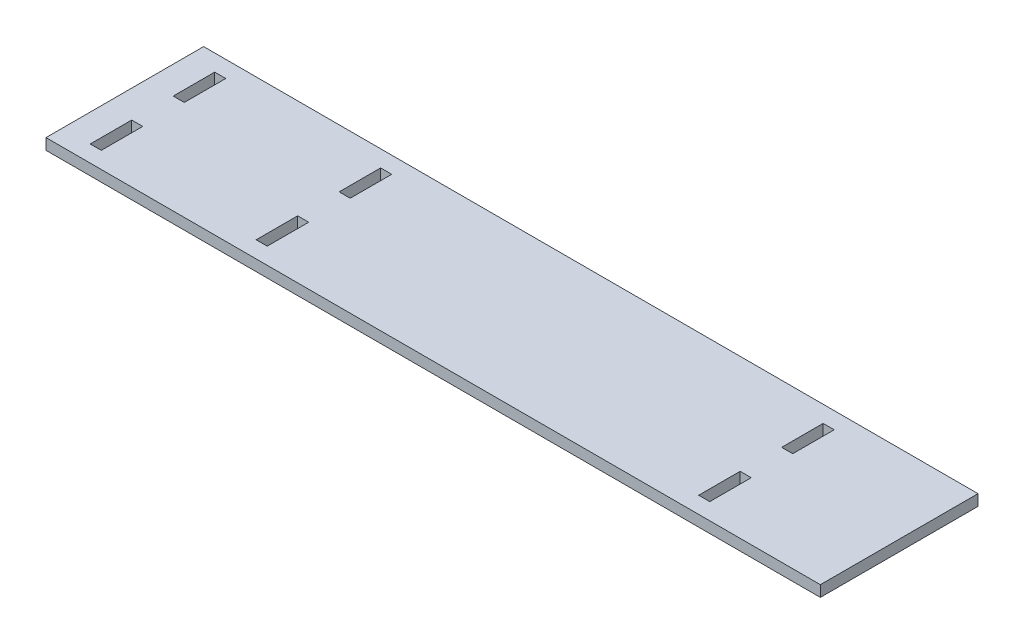
SolidWorks part; units mm, degrees
ref_plane "Front Plane" through (0, 0, 0) normal (0, 0, 1) x (1, 0, 0)
ref_plane "Top Plane" through (0, 0, 0) normal (0, 1, 0) x (1, 0, 0)
ref_plane "Right Plane" through (0, 0, 0) normal (1, 0, 0) x (0, 0, -1)
sketch "Sketch1" plane through (0, 0, 0) normal (0, 1, 0) x (1, 0, 0)
  line L1 (0, 0) -> (280, 0)
  line L2 (0, 0) -> (0, 65)
  line L3 (0, 65) -> (280, 65)
  line L4 (280, 0) -> (280, 65)
  dimension "D1" = 65
  dimension "D2" = 280
extrude "Boss-Extrude1" add sketch "Sketch1" along normal blind 4
sketch "Sketch2" plane through (0, 4, 0) normal (0, 1, 0) x (1, 0, 0)
  line L0 (0, 0) -> (280, 0) construction
  line L1 (74, 0) -> (70, 0)
  line L2 (74, 0) -> (74, 65)
  line L3 (74, 65) -> (70, 65)
  line L4 (70, 0) -> (70, 65)
  line L5 (280, 65) -> (0, 65) construction
  line L6 (0, 65) -> (0, 0) construction
  line L7 (14, 0) -> (14, 65)
  line L8 (70, 55) -> (74, 55)
  line L9 (70, 55) -> (70, 40)
  line L10 (70, 40) -> (74, 40)
  line L11 (74, 55) -> (74, 40)
  line L12 (74, 25) -> (70, 25)
  line L13 (74, 25) -> (74, 10)
  line L14 (74, 10) -> (70, 10)
  line L15 (70, 25) -> (70, 10)
  line L16 (14, 0) -> (10, 0)
  line L17 (10, 0) -> (10, 65)
  line L18 (14, 65) -> (10, 65)
  line L19 (10, 55) -> (10, 40)
  line L20 (10, 55) -> (14, 55)
  line L21 (14, 55) -> (14, 40)
  line L22 (10, 40) -> (14, 40)
  line L23 (14, 25) -> (14, 10)
  line L24 (14, 25) -> (10, 25)
  line L25 (10, 25) -> (10, 10)
  line L26 (14, 10) -> (10, 10)
  line L27 (230, 55) -> (230, 40)
  line L28 (230, 55) -> (234, 55)
  line L29 (234, 55) -> (234, 40)
  line L30 (230, 40) -> (234, 40)
  line L31 (234, 25) -> (234, 10)
  line L32 (234, 25) -> (230, 25)
  line L33 (230, 25) -> (230, 10)
  line L34 (234, 10) -> (230, 10)
  dimension "D1" = 4
  dimension "D2" = 70
  dimension "D3" = 15
  dimension "D4" = 15
  dimension "D5" = 10
  dimension "D6" = 10
  dimension "D7" = 2
extrude "Cut-Extrude1" cut sketch "Sketch2" against normal blind 4 contours L17 L22 L7 L20 | L26 L7 L24 L17 | L14 L2 L12 L4 | L4 L10 L2 L8 | L27 L30 L29 L28 | L34 L31 L32 L33
sketch "Sketch3" plane through (0, 4, 0) normal (0, 1, 0) x (1, 0, 0)
  line L0 (280, 0) -> (280, 65) construction
  line L1 (0, 65) -> (280, 65)
  line L2 (0, 65) -> (0, 61)
  line L3 (0, 61) -> (280, 61)
  line L4 (280, 65) -> (280, 61)
  line L5 (0, 32.5) -> (42.8718, 32.5) construction
  line L6 (0, 65) -> (0, 0) construction
  line L7 (0, 4) -> (280, 4)
  line L8 (280, 0) -> (280, 4)
  line L9 (0, 0) -> (280, 0)
  line L10 (0, 0) -> (0, 4)
  dimension "D1" = 4
extrude "Cut-Extrude2" cut sketch "Sketch3" against normal blind 4
